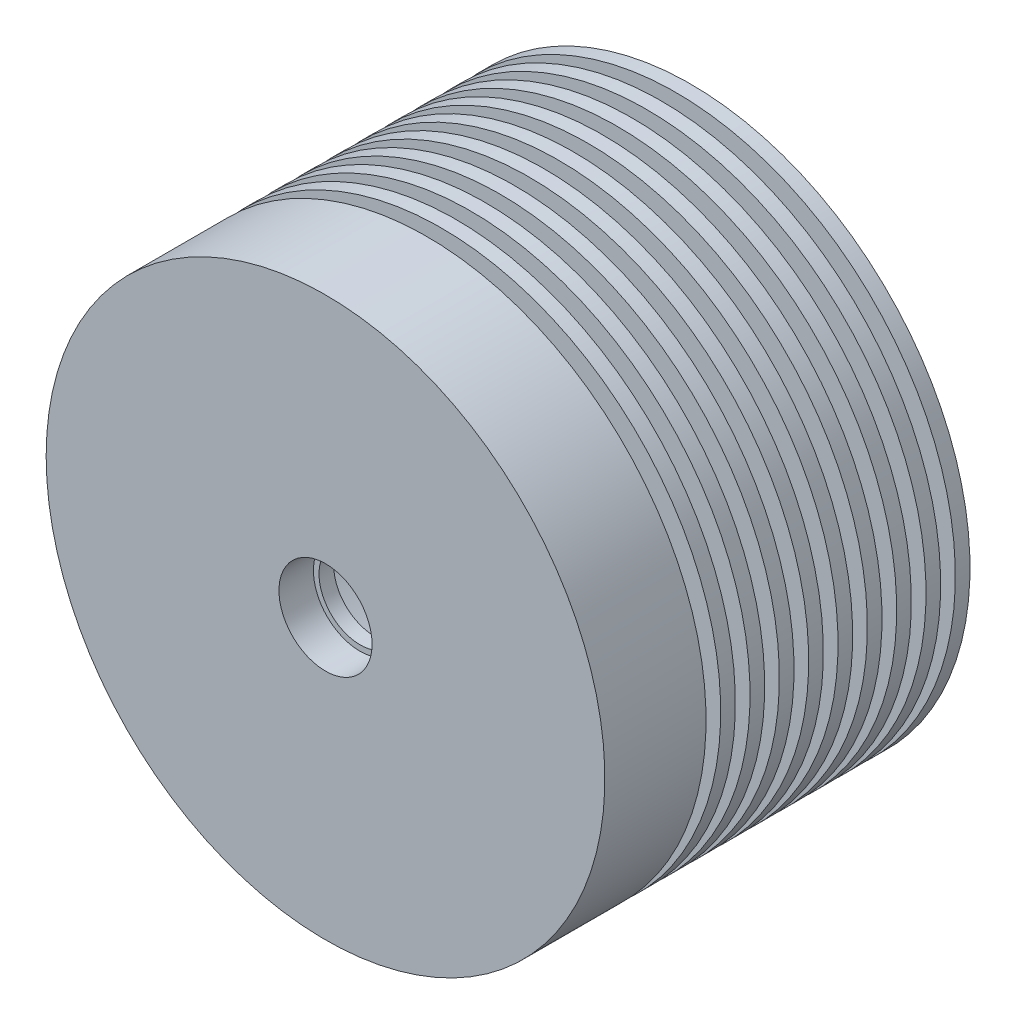
SolidWorks part; units mm, degrees
ref_plane "Plan de face" through (0, 0, 0) normal (0, 0, 1) x (1, 0, 0)
ref_plane "Plan de dessus" through (0, 0, 0) normal (0, 1, 0) x (1, 0, 0)
ref_plane "Plan de droite" through (0, 0, 0) normal (1, 0, 0) x (0, 0, -1)
sketch "Esquisse1" plane through (0, 0, 0) normal (0, 0, 1) x (1, 0, 0)
  circle A0 centre (0, 0) radius 38.1
extrude "Boss.-Extru.1" add sketch "Esquisse1" along normal blind 51.8
sketch "Esquisse2" plane through (0, 0, 51.8) normal (0, 0, 1) x (1, 0, 0)
  circle A0 centre (0, 0) radius 6.35
extrude "Enlèv. mat.-Extru.1" cut sketch "Esquisse2" against normal blind 4.7
sketch "Esquisse3" plane through (0, 0, 47.1) normal (0, 0, 1) x (1, 0, 0)
  circle A0 centre (0, 0) radius 5.588
extrude "Enlèv. mat.-Extru.2" cut sketch "Esquisse3" against normal blind 4
sketch "Esquisse4" plane through (0, 0, 43.1) normal (0, 0, 1) x (1, 0, 0)
  circle A0 centre (0, 0) radius 25.4
extrude "Enlèv. mat.-Extru.3" cut sketch "Esquisse4" against normal blind 43.1
sketch "Esquisse6" plane through (0, 0, 0) normal (0, 0, -1) x (-1, 0, 0)
  circle A0 centre (0, 0) radius 31.75
extrude "Enlèv. mat.-Extru.4" cut sketch "Esquisse6" against normal blind 2 flip side to cut
pattern_linear "Répétition linéaire1" count 10 spacing 4 along (0, 0, 1) of "Enlèv. mat.-Extru.4"
sketch "Esquisse7" plane through (0, 0, 43.1) normal (0, 0, -1) x (-1, 0, 0)
  circle A0 centre (0, 0) radius 25.4
extrude "Enlèv. mat.-Extru.5" cut sketch "Esquisse7" against normal blind 2
